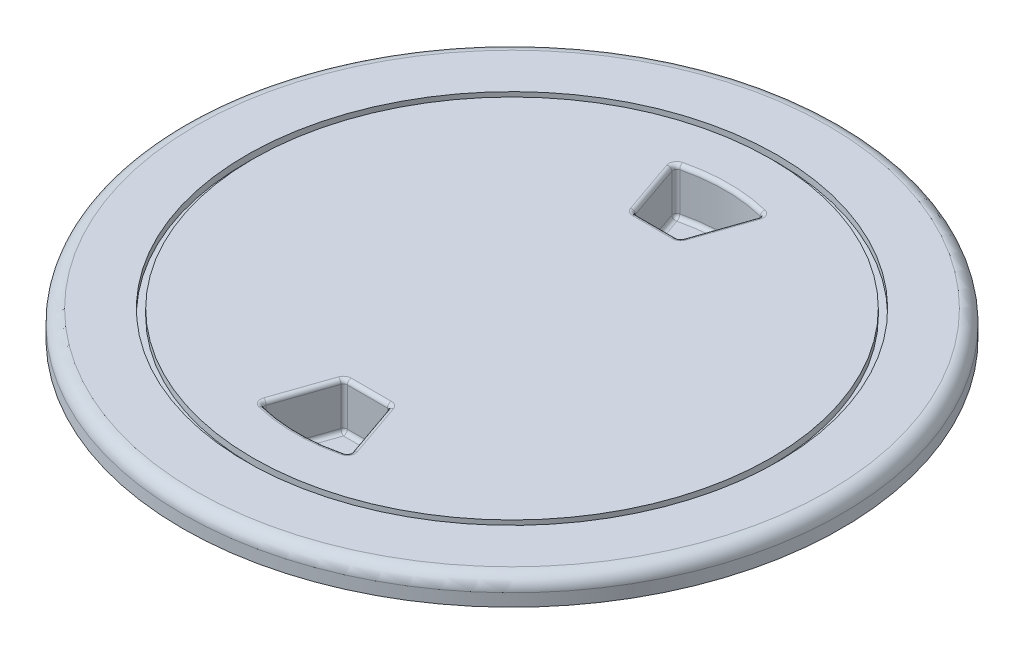
SolidWorks part; units mm, degrees
material "ABS"
ref_plane "Front Plane" through (0, 0, 0) normal (0, 0, 1) x (1, 0, 0)
ref_plane "Top Plane" through (0, 0, 0) normal (0, 1, 0) x (1, 0, 0)
ref_plane "Right Plane" through (0, 0, 0) normal (1, 0, 0) x (0, 0, -1)
sketch "Sketch2" plane through (0, 0, 0) normal (0, 0, 1) x (1, 0, 0)
  line L0 (0, 0) -> (98.25, 0)
  line L1 (137.5, 0) -> (-137.5, 0) construction
  line L2 (98.25, 0) -> (98.25, -2.4614)
  line L3 (98.25, -2.4614) -> (100.75, -2.4614)
  line L4 (100.75, -2.4614) -> (100.75, 0)
  line L5 (100.75, 0) -> (120, 0)
  line L6 (125, -5) -> (125, -9.75)
  line L7 (125, -9.75) -> (98.25, -9.75)
  line L8 (98.25, -9.75) -> (98.25, -27.9)
  line L11 (98.25, -27.9) -> (90, -27.9)
  line L12 (90, -27.9) -> (90, -20.8)
  line L13 (90, -20.8) -> (0, -20.8)
  line L14 (0, -20.8) -> (0, 0)
  arc A0 (120, 0) -> (125, -5) centre (120, -5) cw
  dimension "D1" = 5
  dimension "D2" = 125
  dimension "D3" = 90
  dimension "D4" = 98.25
  dimension "D5" = 27.9
  dimension "D6" = 24.25
  dimension "D7" = 9.75
  dimension "D8" = 20.8
revolve "Revolve1" add sketch "Sketch2" angle 360 about L14
sketch "Sketch4" plane through (0, 0, 0) normal (0, 1, 0) x (1, 0, 0)
  line L0 (-7.6068, 54.85) -> (7.6068, 54.85)
  line L1 (9.0243, 55.8595) -> (16.319, 76.9409)
  line L3 (-16.319, 76.9409) -> (-9.0243, 55.8595)
  line L4 (-16.85, 78.4756) -> (16.85, 78.4756) construction
  line L5 (-15.345, 0) -> (15.345, 0) construction
  line L6 (-16.319, -76.9409) -> (-9.0243, -55.8595)
  line L7 (-7.6068, -54.85) -> (7.6068, -54.85)
  line L8 (9.0243, -55.8595) -> (16.319, -76.9409)
  arc A1 (-15.2593, 78.8881) -> (15.2593, 78.8881) centre (0, 16.769) cw
  arc A2 (9.0243, 55.8595) -> (7.6068, 54.85) centre (7.6068, 56.35) cw
  arc A3 (-16.319, 76.9409) -> (-15.2593, 78.8881) centre (-14.9014, 77.4314) cw
  arc A4 (15.2593, 78.8881) -> (16.319, 76.9409) centre (14.9014, 77.4314) cw
  arc A5 (-7.6068, 54.85) -> (-9.0243, 55.8595) centre (-7.6068, 56.35) cw
  arc A6 (-7.6068, -54.85) -> (-9.0243, -55.8595) centre (-7.6068, -56.35) ccw
  arc A7 (9.0243, -55.8595) -> (7.6068, -54.85) centre (7.6068, -56.35) ccw
  arc A8 (-16.319, -76.9409) -> (-15.2593, -78.8881) centre (-14.9014, -77.4314) ccw
  arc A9 (15.2593, -78.8881) -> (16.319, -76.9409) centre (14.9014, -77.4314) ccw
  arc A10 (-15.2593, -78.8881) -> (15.2593, -78.8881) centre (0, -16.769) ccw
  point P5 (0, 54.85)
  point P6 (0, 80.7348)
  point P10 (8.675, 54.85)
  point P19 (-8.675, 54.85)
  dimension "D5" = 1.5
  dimension "D1" = 17.35
  dimension "D2" = 33.7
  dimension "D4" = 25
  dimension "D3" = 25.8848
  dimension "D6" = 54.85
extrude "Cut-Extrude1" cut sketch "Sketch4" against normal blind 17.5
sketch "Sketch5" plane through (0, -20.8, 0) normal (0, -1, 0) x (1, 0, 0)
  line L0 (16.319, 76.9409) -> (9.0243, 55.8595) construction
  line L1 (7.6068, 54.85) -> (-7.6068, 54.85) construction
  line L2 (-9.0243, 55.8595) -> (-16.319, 76.9409) construction
  line L3 (9.0243, -55.8595) -> (16.319, -76.9409) construction
  line L4 (-16.319, -76.9409) -> (-9.0243, -55.8595) construction
  line L5 (-7.6068, -54.85) -> (7.6068, -54.85) construction
  line L6 (16.319, 76.9409) -> (9.0243, 55.8595) construction
  line L7 (7.6068, 54.85) -> (-7.6068, 54.85) construction
  line L8 (-9.0243, 55.8595) -> (-16.319, 76.9409) construction
  line L9 (9.0243, -55.8595) -> (16.319, -76.9409) construction
  line L10 (-16.319, -76.9409) -> (-9.0243, -55.8595) construction
  line L11 (-7.6068, -54.85) -> (7.6068, -54.85) construction
  line L12 (-7.6068, -51.55) -> (7.6068, -51.55)
  line L13 (-19.4375, -75.8618) -> (-12.1429, -54.7804)
  line L14 (12.1429, -54.7804) -> (19.4375, -75.8618)
  line L15 (-12.1429, 54.7804) -> (-19.4375, 75.8618)
  line L16 (7.6068, 51.55) -> (-7.6068, 51.55)
  line L17 (19.4375, 75.8618) -> (12.1429, 54.7804)
  arc A0 (-15.2593, 78.8881) -> (-16.319, 76.9409) centre (-14.9014, 77.4314) ccw construction
  arc A1 (15.2593, 78.8881) -> (-15.2593, 78.8881) centre (0, 16.769) ccw construction
  arc A2 (16.319, 76.9409) -> (15.2593, 78.8881) centre (14.9014, 77.4314) ccw construction
  arc A3 (7.6068, 54.85) -> (9.0243, 55.8595) centre (7.6068, 56.35) ccw construction
  arc A4 (-9.0243, 55.8595) -> (-7.6068, 54.85) centre (-7.6068, 56.35) ccw construction
  arc A5 (9.0243, -55.8595) -> (7.6068, -54.85) centre (7.6068, -56.35) ccw construction
  arc A6 (15.2593, -78.8881) -> (16.319, -76.9409) centre (14.9014, -77.4314) ccw construction
  arc A7 (-15.2593, -78.8881) -> (15.2593, -78.8881) centre (0, -16.769) ccw construction
  arc A8 (-16.319, -76.9409) -> (-15.2593, -78.8881) centre (-14.9014, -77.4314) ccw construction
  arc A9 (-7.6068, -54.85) -> (-9.0243, -55.8595) centre (-7.6068, -56.35) ccw construction
  arc A10 (-15.2593, 78.8881) -> (-16.319, 76.9409) centre (-14.9014, 77.4314) ccw construction
  arc A11 (15.2593, 78.8881) -> (-15.2593, 78.8881) centre (0, 16.769) ccw construction
  arc A12 (16.319, 76.9409) -> (15.2593, 78.8881) centre (14.9014, 77.4314) ccw construction
  arc A13 (7.6068, 54.85) -> (9.0243, 55.8595) centre (7.6068, 56.35) ccw construction
  arc A14 (-9.0243, 55.8595) -> (-7.6068, 54.85) centre (-7.6068, 56.35) ccw construction
  arc A15 (9.0243, -55.8595) -> (7.6068, -54.85) centre (7.6068, -56.35) ccw construction
  arc A16 (15.2593, -78.8881) -> (16.319, -76.9409) centre (14.9014, -77.4314) ccw construction
  arc A17 (-15.2593, -78.8881) -> (15.2593, -78.8881) centre (0, -16.769) ccw construction
  arc A18 (-16.319, -76.9409) -> (-15.2593, -78.8881) centre (-14.9014, -77.4314) ccw construction
  arc A19 (-7.6068, -54.85) -> (-9.0243, -55.8595) centre (-7.6068, -56.35) ccw construction
  circle A20 centre (0, 0) radius 90 construction
  circle A21 centre (0, 0) radius 90
  arc A22 (12.1429, -54.7804) -> (7.6068, -51.55) centre (7.6068, -56.35) ccw
  arc A23 (-7.6068, -51.55) -> (-12.1429, -54.7804) centre (-7.6068, -56.35) ccw
  arc A24 (-19.4375, -75.8618) -> (-16.0465, -82.0928) centre (-14.9014, -77.4314) ccw
  arc A25 (-16.0465, -82.0928) -> (16.0465, -82.0928) centre (0, -16.769) ccw
  arc A26 (16.0465, -82.0928) -> (19.4375, -75.8618) centre (14.9014, -77.4314) ccw
  arc A27 (-16.0465, 82.0928) -> (-19.4375, 75.8618) centre (-14.9014, 77.4314) ccw
  arc A28 (-12.1429, 54.7804) -> (-7.6068, 51.55) centre (-7.6068, 56.35) ccw
  arc A29 (7.6068, 51.55) -> (12.1429, 54.7804) centre (7.6068, 56.35) ccw
  arc A30 (19.4375, 75.8618) -> (16.0465, 82.0928) centre (14.9014, 77.4314) ccw
  arc A31 (16.0465, 82.0928) -> (-16.0465, 82.0928) centre (0, 16.769) ccw
  dimension "D1" = 3.3
  dimension "D2" = 3.3
extrude "Cut-Extrude2" cut sketch "Sketch5" against normal blind 17.5
fillet "Fillet2" radius 1.5 32 edges at (-16.2189, -17.5, -78.1484) (0, -17.5, -80.7348) (16.2189, -17.5, -78.1484) (12.6716, -17.5, -66.4002) (8.4769, -17.5, -55.1282) (0, -17.5, -54.85) (-8.4769, -17.5, -55.1282) (-16.2189, 0, -78.1484) (0, 0, -80.7348) (16.2189, 0, -78.1484) (12.6716, 0, -66.4002) (8.4769, 0, -55.1282) (0, 0, -54.85) (-8.4769, 0, -55.1282) (-8.4769, -17.5, 55.1282) (0, -17.5, 54.85) (8.4769, -17.5, 55.1282) (12.6716, -17.5, 66.4002) (16.2189, -17.5, 78.1484) (0, -17.5, 80.7348) (-16.2189, -17.5, 78.1484) (-8.4769, 0, 55.1282) (0, 0, 54.85) (8.4769, 0, 55.1282) (12.6716, 0, 66.4002) (16.2189, 0, 78.1484) (0, 0, 80.7348) (-16.2189, 0, 78.1484) (-12.6716, -17.5, -66.4002) (-12.6716, 0, -66.4002) (-12.6716, -17.5, 66.4002) (-12.6716, 0, 66.4002)
fillet "Fillet4" radius 4.8 16 edges at (-10.3912, -20.8, -52.4401) (0, -20.8, -51.55) (10.3912, -20.8, -52.4401) (15.7902, -20.8, -65.3211) (19.1175, -20.8, -79.7259) (0, -20.8, -84.0348) (-19.1175, -20.8, -79.7259) (-19.1175, -20.8, 79.7259) (0, -20.8, 84.0348) (19.1175, -20.8, 79.7259) (15.7902, -20.8, 65.3211) (10.3912, -20.8, 52.4401) (0, -20.8, 51.55) (-10.3912, -20.8, 52.4401) (-15.7902, -20.8, -65.3211) (-15.7902, -20.8, 65.3211)
equation "\"D2@Sketch2\"=250/2"
equation "\"D3@Sketch2\"=90"
equation "\"D4@Sketch2\"=196.50/2"
equation "\"D6@Sketch4\"=109.7/2"
